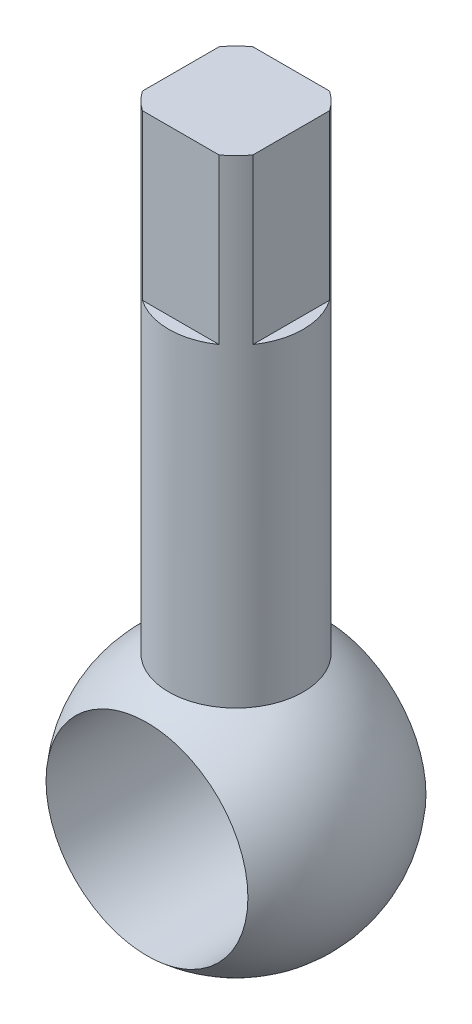
SolidWorks part; units mm, degrees
ref_plane "Alzado" through (0, 0, 0) normal (0, 0, 1) x (1, 0, 0)
ref_plane "Planta" through (0, 0, 0) normal (0, 1, 0) x (1, 0, 0)
ref_plane "Vista lateral" through (0, 0, 0) normal (1, 0, 0) x (0, 0, -1)
sketch "Croquis1" plane through (0, 0, 0) normal (0, 0, 1) x (1, 0, 0)
  line L0 (0, 0) -> (0, 137.668)
  line L1 (0, 137.668) -> (-12.7, 137.668)
  line L2 (-12.7, 137.668) -> (-12.7, 47.397)
  arc A0 (-12.7, 47.397) -> (0, 0) centre (0, 25.4) ccw
  dimension "D3" = 25.4
  dimension "D1" = 137.668
  dimension "D2" = 12.7
revolve "Revolución1" add sketch "Croquis1" angle 360 about L0
sketch "Croquis2" plane through (0, 0, 0) normal (0, 0, 1) x (1, 0, 0)
  circle A0 centre (0, 25.4) radius 19.05
  arc A1 (-12.7, 47.397) -> (12.7, 47.397) centre (0, 25.4) ccw construction
  dimension "D1" = 38.1
extrude "Cortar-Extruir1" cut sketch "Croquis2" against normal through all both and the other way through all
sketch "Croquis3" plane through (0, 137.668, 0) normal (0, 1, 0) x (1, 0, 0)
  line L1 (-7.239, 10.4349) -> (7.239, 10.4349)
  line L2 (-7.239, 10.4349) -> (-7.239, 15.0069)
  line L3 (-7.239, 15.0069) -> (7.239, 15.0069)
  line L4 (7.239, 10.4349) -> (7.239, 15.0069)
  circle A0 centre (0, 0) radius 12.7 construction
  circle A1 centre (0, 0) radius 12.7 construction
  dimension "D1" = 14.478
  dimension "D2" = 4.572
extrude "Cortar-Extruir2" cut sketch "Croquis3" against normal blind 30.988
pattern_circular "MatrizC1" count 4 over 360 about axis through (0, 0, 0) along (0, 1, 0) of "Cortar-Extruir2"
